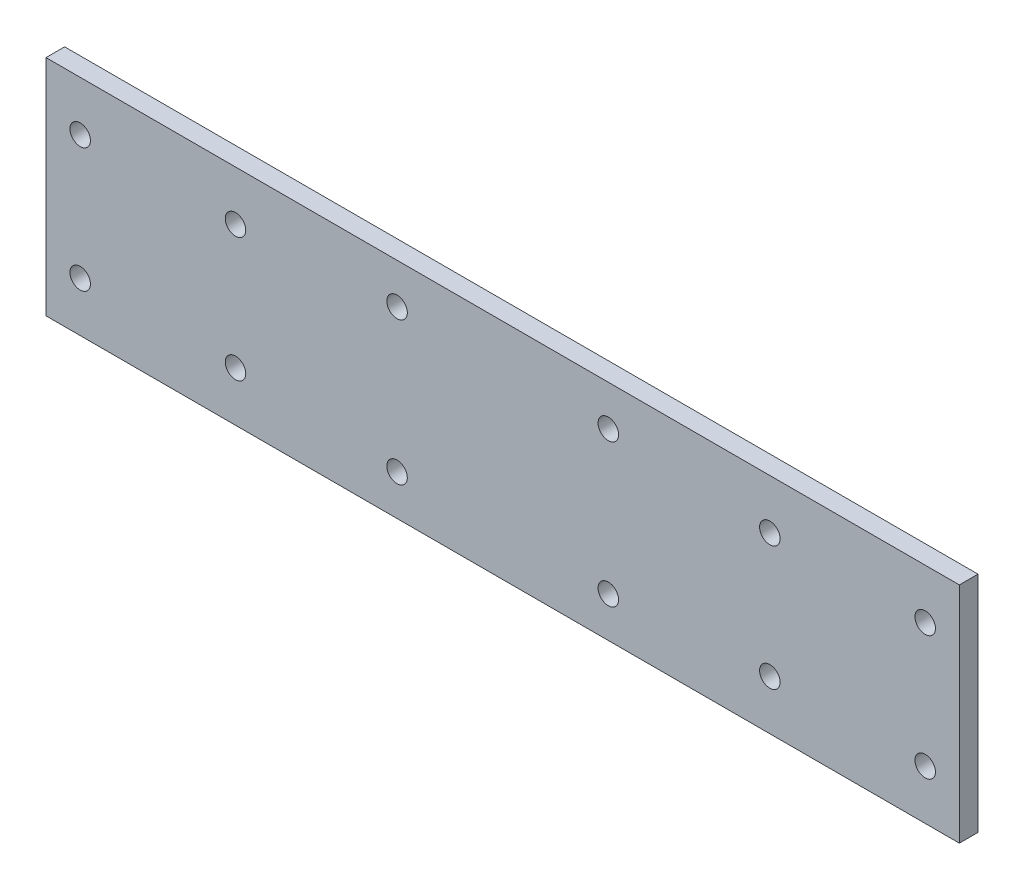
SolidWorks part; units mm, degrees
ref_plane "前视基准面" through (0, 0, 0) normal (0, 0, 1) x (1, 0, 0)
ref_plane "上视基准面" through (0, 0, 0) normal (0, 1, 0) x (1, 0, 0)
ref_plane "右视基准面" through (0, 0, 0) normal (1, 0, 0) x (0, 0, -1)
sketch "草图1" plane through (0, 0, 0) normal (0, 0, 1) x (1, 0, 0)
  line L0 (0, -1000) -> (0, 49000) construction
  line L1 (-73.5, 18) -> (73.5, 18)
  line L2 (-73.5, 18) -> (-73.5, -18)
  line L3 (-73.5, -18) -> (73.5, -18)
  line L4 (73.5, 18) -> (73.5, -18)
  line L5 (-73.5, 18) -> (73.5, -18) construction
  line L6 (-73.5, -18) -> (73.5, 18) construction
  line L7 (-1000, 0) -> (49000, 0) construction
  point P0 (0, 0)
  dimension "D1" = 36
  dimension "D2" = 147
extrude "凸台-拉伸1" add sketch "草图1" along normal blind 3
sketch "草图2" plane through (0, 0, 3) normal (0, 0, 1) x (1, 0, 0)
  line L0 (0, -1000) -> (0, 49000) construction
  line L1 (-1000, 0) -> (49000, 0) construction
  circle A0 centre (-17, 11.5) radius 2
  dimension "D1" = 17
  dimension "D2" = 11.5
hole_wizard "M4 螺纹孔的螺纹孔钻头1" positions "3D草图1" profile "草图3" hole size "M4" standard "GB"
sketch3d "3D草图1"
  point P0 (-17, 11.5, 3)
sketch "草图3" plane through (-17, 11.5, 3) normal (1, 0, 0) x (0, -1, 0)
  line L0 (0, 0) -> (0, 10.9914)
  line L1 (0, 10.9914) -> (1.65, 10)
  line L2 (1.65, 10) -> (1.65, 0)
  line L5 (1.65, 0) -> (0, 0)
  line L10 (0, 10.9914) -> (-1.65, 10) construction
  line L11 (0, -6.35) -> (0, 107.95) construction
  dimension "孔直径" = 3.3
  dimension "孔深度" = 10
  dimension "导头角度" = 118
mirror "镜向1" about plane through (0, 0, 0) normal (0, 1, 0) of "M4 螺纹孔的螺纹孔钻头1"
mirror "镜向2" about plane through (0, 0, 0) normal (1, 0, 0) of "镜向1", "M4 螺纹孔的螺纹孔钻头1"
sketch "草图4" plane through (0, 0, 3) normal (0, 0, 1) x (1, 0, 0)
  line L1 (-73.5, 18) -> (-73.5, -18) construction
  line L3 (-201000, 0) -> (249000, 0) construction
  circle A0 centre (-68, -10) radius 2
  circle A1 centre (-43, -10) radius 2
  dimension "D1" = 10
  dimension "D2" = 5.5
  dimension "D3" = 25
hole_wizard "M4 螺纹孔的螺纹孔钻头2" positions "3D草图2" profile "草图5" hole size "M4" standard "GB"
sketch3d "3D草图2"
  point P0 (-68, -10, 3)
  point P3 (-43, -10, 3)
sketch "草图5" plane through (-68, -10, 3) normal (1, 0, 0) x (0, -1, 0)
  line L0 (0, 0) -> (0, 10.9914)
  line L1 (0, 10.9914) -> (1.65, 10)
  line L2 (1.65, 10) -> (1.65, 0)
  line L5 (1.65, 0) -> (0, 0)
  line L10 (0, 10.9914) -> (-1.65, 10) construction
  line L11 (0, -6.35) -> (0, 107.95) construction
  dimension "孔直径" = 3.3
  dimension "孔深度" = 10
  dimension "导头角度" = 118
mirror "镜向3" about plane through (0, 0, 0) normal (0, 1, 0) of "M4 螺纹孔的螺纹孔钻头2"
mirror "镜向4" about plane through (0, 0, 0) normal (1, 0, 0) of "镜向3", "M4 螺纹孔的螺纹孔钻头2"
